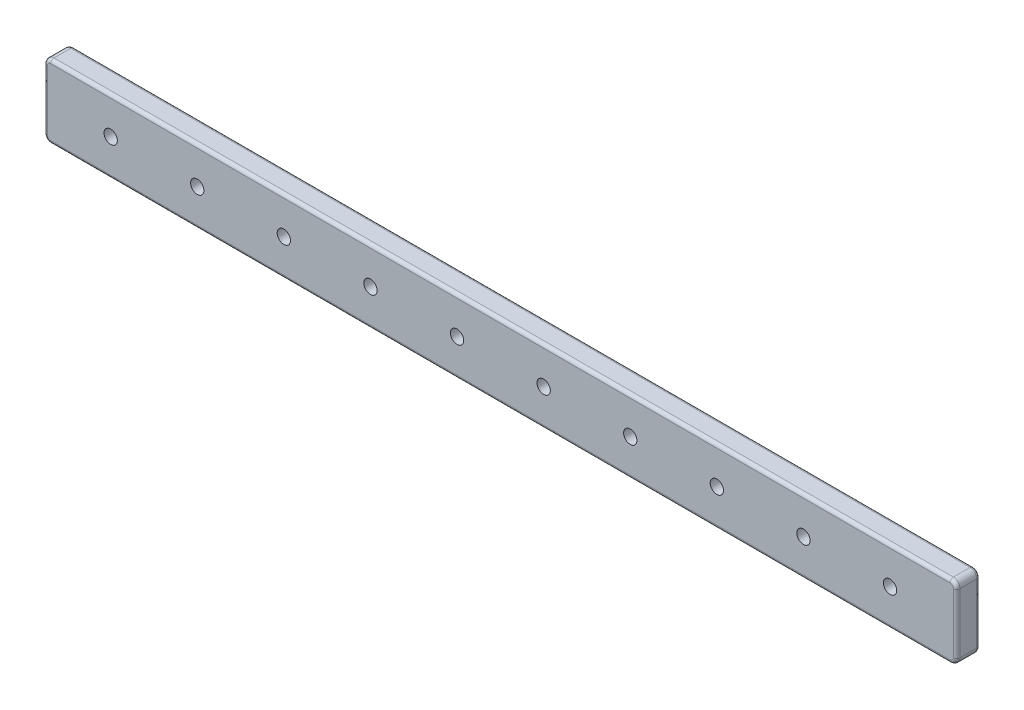
SolidWorks part; units mm, degrees
ref_plane "Front Plane" through (0, 0, 0) normal (0, 0, 1) x (1, 0, 0)
ref_plane "Top Plane" through (0, 0, 0) normal (0, 1, 0) x (1, 0, 0)
ref_plane "Right Plane" through (0, 0, 0) normal (1, 0, 0) x (0, 0, -1)
sketch "Sketch1" plane through (0, 0, 0) normal (0, 0, 1) x (1, 0, 0)
  line L1 (-42.7962, 15.1352) -> (94.2038, 15.1352)
  line L2 (-42.7962, 15.1352) -> (-42.7962, 4.1352)
  line L3 (-42.7962, 4.1352) -> (94.2038, 4.1352)
  line L4 (94.2038, 15.1352) -> (94.2038, 4.1352)
  dimension "D1" = 137
  dimension "D2" = 11
extrude "Boss-Extrude1" add sketch "Sketch1" along normal blind 3.5 contours L1 L4 L3 L2
sketch "Sketch2" plane through (0, 0, 0) normal (0, 0, -1) x (-1, 0, 0)
  line L0 (-94.2038, 9.6352) -> (42.7962, 9.6352) construction
  line L1 (-94.2038, 15.1352) -> (-94.2038, 4.1352) construction
  line L2 (42.7962, 15.1352) -> (42.7962, 4.1352) construction
  line L3 (42.7962, 9.6352) -> (70.047, 9.6352) construction
  circle A0 centre (-84.2038, 9.6352) radius 1
  circle A1 centre (-71.2038, 9.6352) radius 1
  circle A2 centre (-58.2038, 9.6352) radius 1
  circle A3 centre (-45.2038, 9.6352) radius 1
  circle A4 centre (-32.2038, 9.6352) radius 1
  circle A5 centre (-19.2038, 9.6352) radius 1
  circle A6 centre (-6.2038, 9.6352) radius 1
  circle A7 centre (6.7962, 9.6352) radius 1
  circle A8 centre (19.7962, 9.6352) radius 1
  circle A9 centre (32.7962, 9.6352) radius 1
  dimension "D1" = 2
  dimension "D3" = 10
  dimension "D2" = 10
extrude "Cut-Extrude1" cut sketch "Sketch2" against normal blind 3.5
fillet "Fillet1" radius 1 4 edges at (-42.7962, 4.1352, 1.75) (-42.7962, 15.1352, 1.75) (94.2038, 4.1352, 1.75) (94.2038, 15.1352, 1.75)
fillet "Fillet2" radius 0.5 16 edges at (-42.5033, 14.8423, 0) (-42.7962, 9.6352, 0) (-42.5033, 4.4281, 0) (25.7038, 4.1352, 0) (93.9109, 4.4281, 0) (94.2038, 9.6352, 0) (93.9109, 14.8423, 0) (-42.5033, 14.8423, 3.5) (-42.7962, 9.6352, 3.5) (-42.5033, 4.4281, 3.5) (25.7038, 4.1352, 3.5) (93.9109, 4.4281, 3.5) (94.2038, 9.6352, 3.5) (93.9109, 14.8423, 3.5) (25.7038, 15.1352, 0) (25.7038, 15.1352, 3.5)
